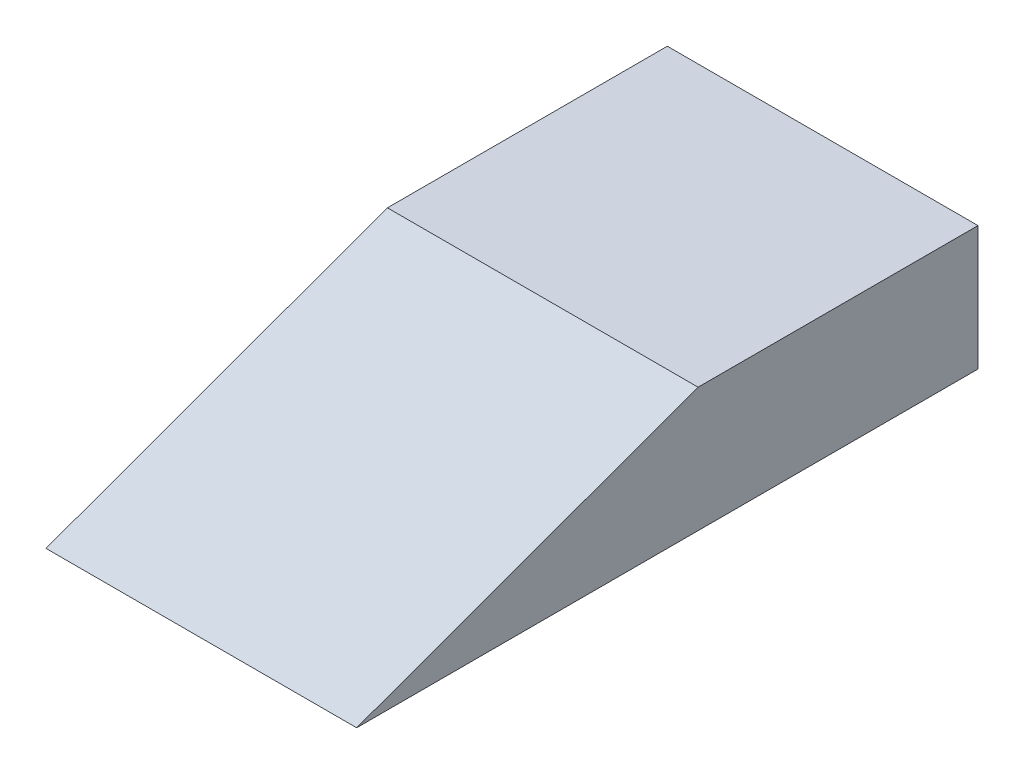
SolidWorks part; units mm, degrees
ref_plane "Front Plane" through (0, 0, 0) normal (0, 0, 1) x (1, 0, 0)
ref_plane "Top Plane" through (0, 0, 0) normal (0, 1, 0) x (1, 0, 0)
ref_plane "Right Plane" through (0, 0, 0) normal (1, 0, 0) x (0, 0, -1)
sketch "Sketch1" plane through (0, 0, 0) normal (1, 0, 0) x (0, 0, -1)
  line L0 (0, 0) -> (549.4955, 200)
  line L1 (549.4955, 200) -> (1000, 200)
  line L2 (1000, 200) -> (1000, 0)
  line L3 (1000, 0) -> (0, 0)
  dimension "D1" = 20
  dimension "D2" = 200
  dimension "D3" = 1000
extrude "Boss-Extrude1" add sketch "Sketch1" along normal blind 500
